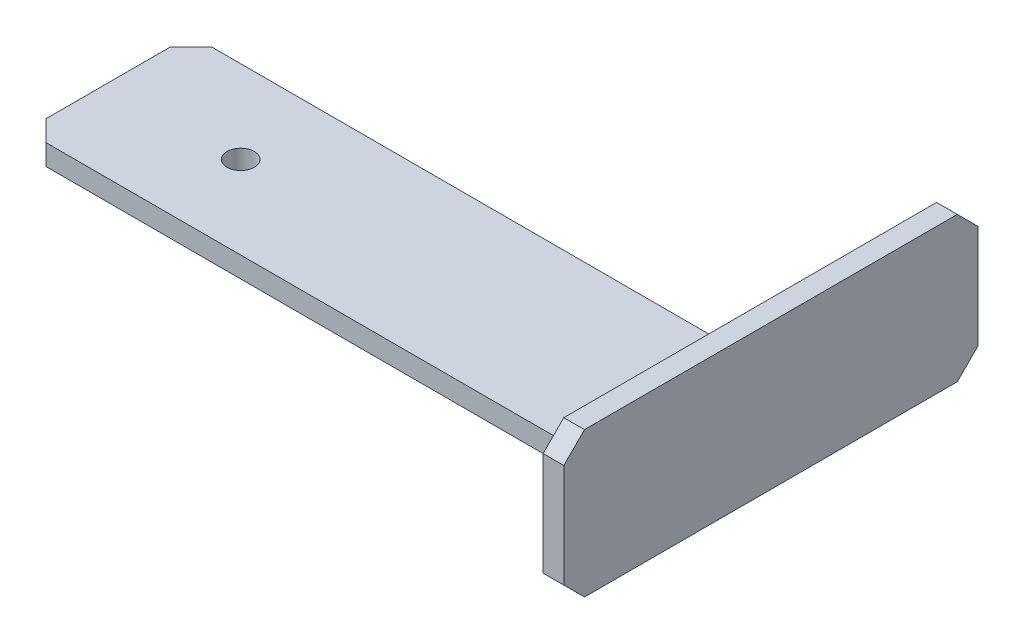
SolidWorks part; units mm, degrees
ref_plane "Front Plane" through (0, 0, 0) normal (0, 0, 1) x (1, 0, 0)
ref_plane "Top Plane" through (0, 0, 0) normal (0, 1, 0) x (1, 0, 0)
ref_plane "Right Plane" through (0, 0, 0) normal (1, 0, 0) x (0, 0, -1)
sketch "Sketch1" plane through (0, 0, 0) normal (0, 1, 0) x (1, 0, 0)
  line L1 (0, 0) -> (160, 0)
  line L2 (0, 0) -> (0, 40)
  line L3 (0, 40) -> (160, 40)
  line L4 (160, 0) -> (160, 40)
  circle A0 centre (32, 20) radius 3.302
  point P7 (32, 24.8709)
  point P11 (0, 20)
  dimension "D4" = 6.604
  dimension "D1" = 40
  dimension "D2" = 160
  dimension "D3" = 32
extrude "Boss-Extrude1" add sketch "Sketch1" along normal blind 5
sketch "Sketch2" plane through (0, 0, 0) normal (0, -1, 0) x (1, 0, 0)
  line L0 (160, 0) -> (160, -40) construction
  line L1 (155, -70) -> (160, -70)
  line L2 (155, -70) -> (155, 30)
  line L3 (155, 30) -> (160, 30)
  line L4 (160, -70) -> (160, 30)
  point P6 (160, -20)
  point P7 (160, -20)
  dimension "D1" = 5
  dimension "D2" = 100
extrude "Boss-Extrude2" add sketch "Sketch2" against normal blind 35
chamfer "Chamfer1" distance 5 angle 45 8 edges at (157.5, 0, -70) (157.5, 35, -70) (157.5, 0, 30) (157.5, 35, 30) (0, 2.5, -40) (0, 2.5, 0) (155, 2.5, 0) (155, 2.5, -40)
